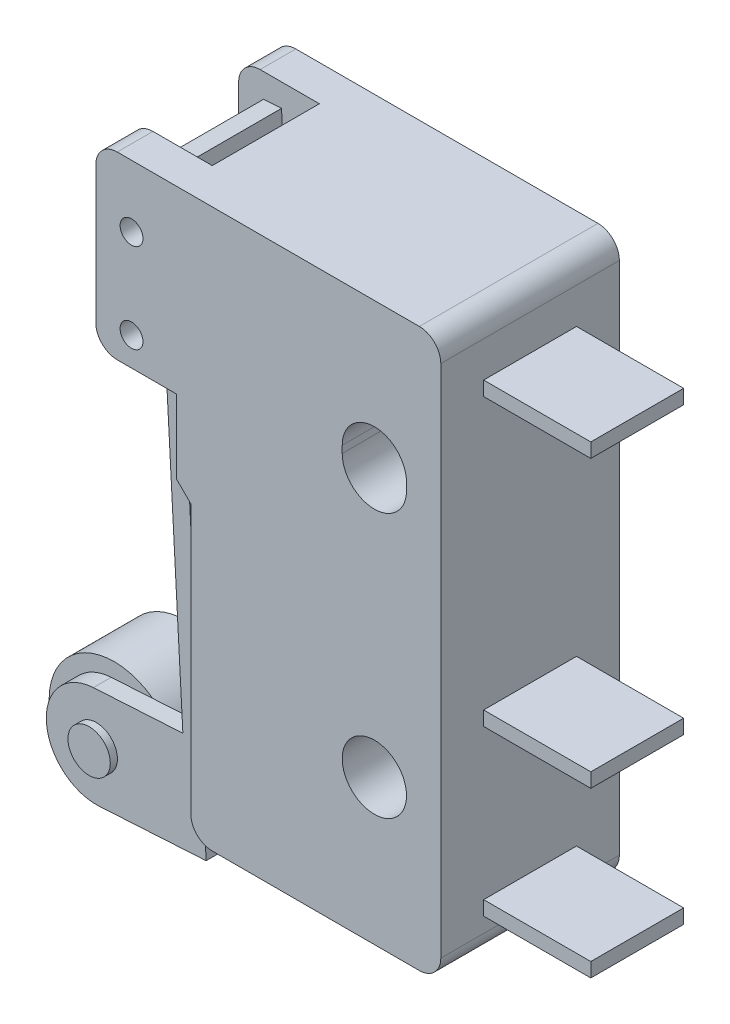
SolidWorks part; units mm, degrees
ref_plane "Plane1" through (0, 0, 0) normal (0, 0, 1) x (1, 0, 0)
ref_plane "Plane2" through (0, 0, 0) normal (0, 1, 0) x (-1, 0, 0)
ref_plane "Plane3" through (0, 0, 0) normal (1, 0, 0) x (0, 0, -1)
sketch "Sketch1" plane through (0, 0, 0) normal (0, 0, 1) x (1, 0, 0)
  line L15 (15.7482, 1.4054) -> (15.7482, 10.9558)
  line L16 (24.6382, 1.4054) -> (24.6382, 19.7188)
  line L18 (23.8762, 20.4808) -> (13.132, 20.4808)
  line L19 (12.37, 19.7188) -> (12.37, 14.842)
  line L24 (15.7482, 10.9558) -> (15.2402, 11.4638)
  line L26 (13.132, 14.08) -> (15.2402, 14.08)
  line L27 (15.2402, 11.4638) -> (15.2402, 14.08)
  line L30 (23.419, 15.1976) -> (23.419, 15.4516)
  line L31 (21.133, 15.1976) -> (21.133, 15.4516)
  line L39 (23.8762, 0.6434) -> (16.5102, 0.6434)
  arc A11 (24.6382, 19.7188) -> (23.8762, 20.4808) centre (23.8762, 19.7188) ccw
  arc A12 (13.132, 20.4808) -> (12.37, 19.7188) centre (13.132, 19.7188) ccw
  arc A13 (12.37, 14.842) -> (13.132, 14.08) centre (13.132, 14.842) ccw
  circle A14 centre (13.64, 18.271) radius 0.4066
  circle A15 centre (13.64, 15.096) radius 0.4066
  arc A17 (21.133, 15.1976) -> (23.419, 15.1976) centre (22.276, 15.1976) ccw
  arc A18 (23.419, 15.4516) -> (21.133, 15.4516) centre (22.276, 15.4516) ccw
  arc A25 (15.7482, 1.4054) -> (16.5102, 0.6434) centre (16.5102, 1.4054) ccw
  circle A26 centre (22.276, 5.7996) radius 1.143
  arc A27 (23.8762, 0.6434) -> (24.6382, 1.4054) centre (23.8762, 1.4054) ccw
  dimension "D1" = 8.89
  dimension "D2" = 19.8374
extrude "Base-Extrude" add sketch "Sketch1" against normal blind 6.35
sketch "Sketch2" plane through (0, 20.4808, 0) normal (0, 1, 0) x (-1, 0, 0)
  line L0 (-12.37, -6.35) -> (-12.37, 0) construction
  line L1 (-15.2402, -6.35) -> (-15.2402, 0) construction
  line L2 (-15.2402, -5.08) -> (-15.2402, -1.27)
  line L3 (-15.2402, -1.27) -> (-12.37, -1.27)
  line L4 (-12.37, -1.27) -> (-12.37, -5.08)
  line L5 (-12.37, -5.08) -> (-15.2402, -5.08)
  line L6 (-23.8762, 0) -> (-13.132, 0) construction
  line L7 (-23.8762, -6.35) -> (-13.132, -6.35) construction
  dimension "D1" = 1.27
  dimension "D2" = 1.27
extrude "Cut-Extrude1" cut sketch "Sketch2" against normal through all
sketch "Sketch3" plane through (24.6382, 0, 0) normal (1, 0, 0) x (0, 0, -1)
  line L0 (4.826, 18.4488) -> (4.826, 17.9408)
  line L1 (1.524, 18.4488) -> (1.524, 17.9408)
  line L2 (1.524, 18.4488) -> (4.826, 18.4488)
  line L3 (1.524, 17.9408) -> (4.826, 17.9408)
  line L4 (1.524, 8.2888) -> (4.826, 8.2888)
  line L5 (1.524, 7.7808) -> (4.826, 7.7808)
  line L6 (1.524, 2.4468) -> (4.826, 2.4468)
  line L7 (1.524, 1.9388) -> (4.826, 1.9388)
  line L8 (1.524, 2.4468) -> (1.524, 1.9388)
  line L9 (1.524, 8.2888) -> (1.524, 7.7808)
  line L10 (4.826, 8.2888) -> (4.826, 7.7808)
  line L11 (5.08, 20.4808) -> (1.27, 20.4808) construction
  line L12 (4.826, 2.4468) -> (4.826, 1.9388)
  line L13 (0, 1.4054) -> (0, 19.7188) construction
  dimension "D1" = 3.302
  dimension "D2" = 0.508
  dimension "D3" = 0.508
  dimension "D4" = 0.508
  dimension "D5" = 2.54
  dimension "D6" = 12.7
  dimension "D7" = 18.542
  dimension "D8" = 1.524
  dimension "D9" = 3.302
extrude "Boss-Extrude1" add sketch "Sketch3" along normal blind 3.81
ref_plane "Plane4" through (0, 0, -5.08) normal (0, 0, -1) x (-1, 0, 0)
sketch "Sketch4" plane through (0, 0, -5.08) normal (0, 0, 1) x (1, 0, 0)
  line L0 (13.2599, 19.6309) -> (14.1961, 2.4777)
  line L1 (13.894, 19.6655) -> (13.2599, 19.6309)
  line L2 (13.894, 19.6655) -> (15.0238, -1.0353)
  line L16 (11.2203, -1.2584) -> (15.0238, -1.0353)
  line L17 (11.0126, 2.2915) -> (14.1961, 2.4777)
  arc A12 (11.0126, 2.2915) -> (11.2203, -1.2584) centre (11.1165, 0.5165) ccw
  dimension "D6" = 1.778
  dimension "D1" = 0.635
  dimension "D4" = 0.635
  dimension "D5" = 3.8169
extrude "Boss-Extrude2" add sketch "Sketch4" along normal up to surface (3.81 mm away)
sketch "Sketch5" plane through (-0.096, 1.6417, 0) normal (-0.0584, 0.9983, 0) x (-0.9983, -0.0584, 0)
  line L2 (-14.3165, -1.27) -> (-14.3165, -5.08) construction
  line L3 (-14.3165, -1.905) -> (-14.3165, -4.445)
  line L4 (-8.146, -1.905) -> (-8.146, -4.445)
  line L8 (-14.3165, -1.905) -> (-8.146, -1.905)
  line L9 (-14.3165, -4.445) -> (-8.146, -4.445)
extrude "Cut-Extrude2" cut sketch "Sketch5" against normal blind 6.096
sketch "Sketch6" plane through (0, 0, -4.445) normal (0, 0, 1) x (1, 0, 0)
  circle A0 centre (11.1165, 0.5165) radius 2.3114
  arc A1 (11.0126, 2.2915) -> (11.2203, -1.2584) centre (11.1165, 0.5165) ccw construction
  dimension "D1" = 4.6228
extrude "Boss-Extrude3" add sketch "Sketch6" along normal up to surface (2.54 mm away)
sketch "Sketch7" plane through (0, 0, -1.27) normal (0, 0, 1) x (1, 0, 0)
  circle A0 centre (11.1165, 0.5165) radius 0.7526
  arc A1 (11.0126, 2.2915) -> (11.2203, -1.2584) centre (11.1165, 0.5165) ccw construction
  dimension "D1" = 1.5052
extrude "Boss-Extrude4" add sketch "Sketch7" along normal blind 0.254 and the other way blind 4.064
